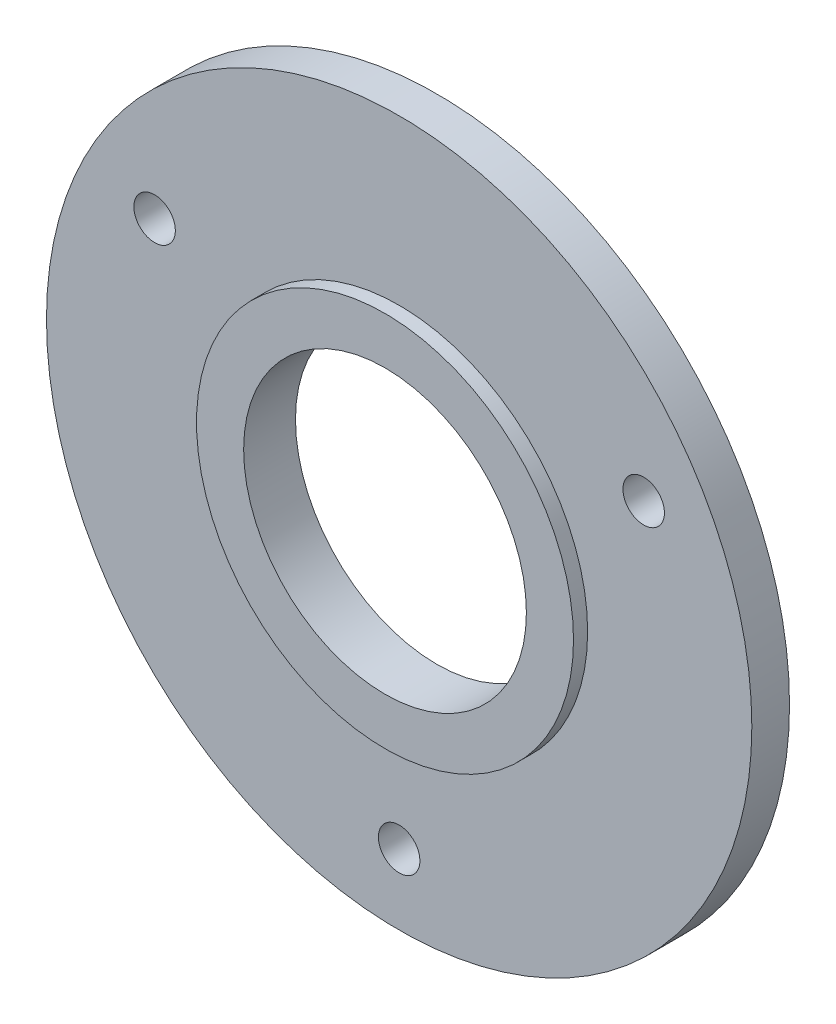
SolidWorks part; units mm, degrees
ref_plane "Front" through (0, 0, 0) normal (0, 0, 1) x (1, 0, 0)
ref_plane "Top" through (0, 0, 0) normal (0, 1, 0) x (1, 0, 0)
ref_plane "Right" through (0, 0, 0) normal (1, 0, 0) x (0, 0, -1)
sketch "Sketch1" plane through (0, 0, 0) normal (0, 0, 1) x (1, 0, 0)
  line L0 (0, 0) -> (0, -14.98) construction
  circle A0 centre (0, 0) radius 18.71
  circle A1 centre (0, -14.98) radius 1.1
  circle A2 centre (-12.9731, 7.49) radius 1.1
  circle A3 centre (12.9731, 7.49) radius 1.1
  circle A4 centre (0, 0) radius 7.5
  dimension "D1" = 37.42
  dimension "D2" = 2.2
  dimension "D5" = 15
  dimension "D4" = 14.98
  dimension "D3" = 3
extrude "Boss-Extrude1" add sketch "Sketch1" along normal blind 2
sketch "Sketch2" plane through (0, 0, 2) normal (0, 0, 1) x (1, 0, 0)
  circle A0 centre (0, 0) radius 10
  circle A1 centre (0, 0) radius 7.5 construction
  circle A2 centre (0, 0) radius 7.5
  dimension "D1" = 20
extrude "Boss-Extrude2" add sketch "Sketch2" along normal blind 0.75
